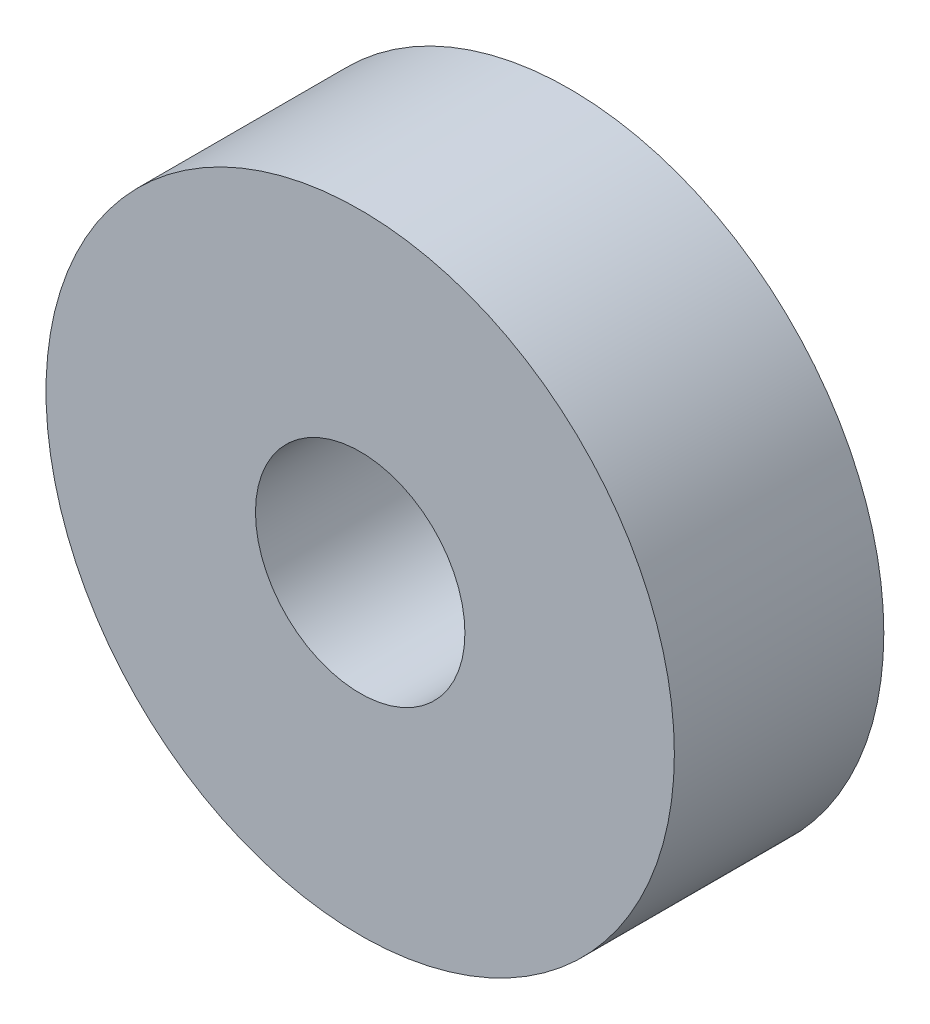
SolidWorks part; units mm, degrees
ref_plane "前视基准面" through (0, 0, 0) normal (0, 0, 1) x (1, 0, 0)
ref_plane "上视基准面" through (0, 0, 0) normal (0, 1, 0) x (1, 0, 0)
ref_plane "右视基准面" through (0, 0, 0) normal (1, 0, 0) x (0, 0, -1)
sketch "草图1" plane through (0, 0, 0) normal (0, 0, 1) x (1, 0, 0)
  circle A0 centre (0, 0) radius 2
  circle A1 centre (0, 0) radius 6
  dimension "D1" = 4
  dimension "D2" = 12
extrude "凸台-拉伸1" add sketch "草图1" along normal blind 4 contours A1
